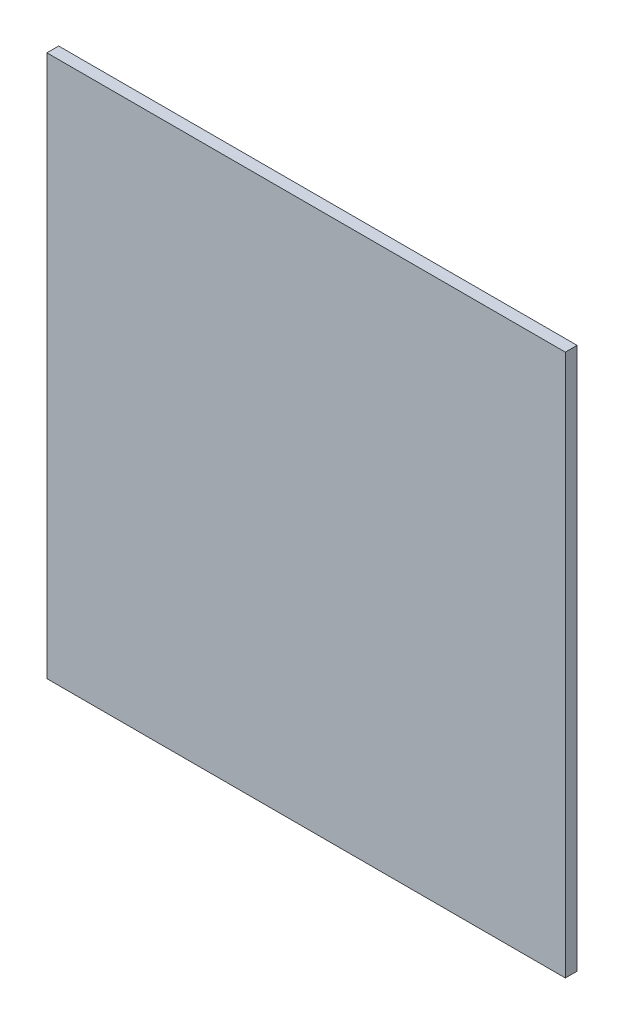
SolidWorks part; units mm, degrees
material "Acrylic (Medium-high impact)"
ref_plane "Front Plane" through (0, 0, 0) normal (0, 0, 1) x (1, 0, 0)
ref_plane "Top Plane" through (0, 0, 0) normal (0, 1, 0) x (1, 0, 0)
ref_plane "Right Plane" through (0, 0, 0) normal (1, 0, 0) x (0, 0, -1)
sketch "Sketch1" plane through (0, 0, 0) normal (0, 0, 1) x (1, 0, 0)
  line L1 (0, 0) -> (558.8, 0)
  line L2 (0, 0) -> (0, 584.2)
  line L3 (0, 584.2) -> (558.8, 584.2)
  line L4 (558.8, 0) -> (558.8, 584.2)
  dimension "D1" = 558.8
  dimension "D2" = 584.2
extrude "Boss-Extrude1" add sketch "Sketch1" along normal blind 12.7
